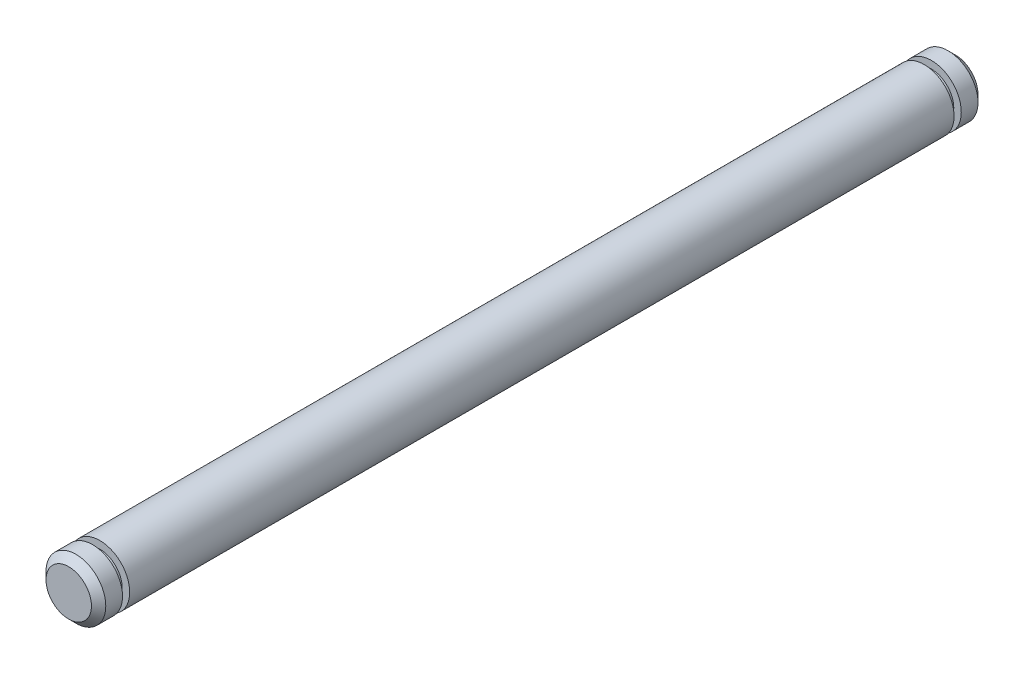
SolidWorks part; units mm, degrees
ref_plane "Front" through (0, 0, 0) normal (0, 0, 1) x (1, 0, 0)
ref_plane "Top" through (0, 0, 0) normal (0, 1, 0) x (1, 0, 0)
ref_plane "Right" through (0, 0, 0) normal (1, 0, 0) x (0, 0, -1)
sketch "Sketch1" plane through (0, 0, 0) normal (0, 0, 1) x (1, 0, 0)
  circle A0 centre (0, 0) radius 1.5875
  dimension "D1" = 3.175
extrude "Boss-Extrude1" add sketch "Sketch1" along normal mid plane 43.7845
sketch "Sketch2" plane through (0, 0, 21.8923) normal (0, 0, 1) x (1, 0, 0)
  circle A0 centre (0, 0) radius 1.1913
  dimension "D1" = 2.3825
extrude "Boss-Extrude2" add sketch "Sketch2" along normal blind 0.381
sketch "Sketch3" plane through (0, 0, 22.2733) normal (0, 0, 1) x (1, 0, 0)
  circle A0 centre (0, 0) radius 1.5875 construction
  circle A1 centre (0, 0) radius 1.5875
extrude "Boss-Extrude3" add sketch "Sketch3" along normal blind 1.27
chamfer "Chamfer1" distance 0.381 1 edges at (1.5875, 0, 23.5433)
mirror "Mirror1" about plane through (0, 0, 0) normal (0, 0, 1) of "Chamfer1", "Boss-Extrude3", "Boss-Extrude2"
